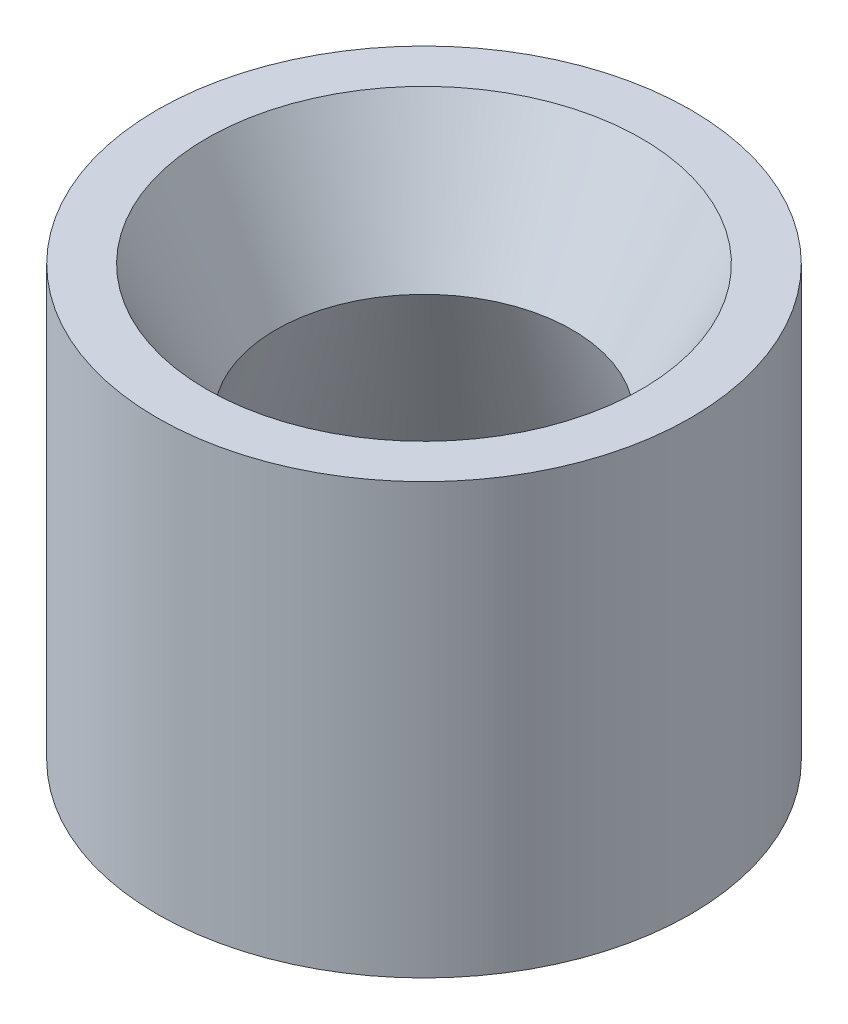
SolidWorks part; units mm, degrees
ref_plane "Front Plane" through (0, 0, 0) normal (0, 0, 1) x (1, 0, 0)
ref_plane "Top Plane" through (0, 0, 0) normal (0, 1, 0) x (1, 0, 0)
ref_plane "Right Plane" through (0, 0, 0) normal (1, 0, 0) x (0, 0, -1)
sketch "Sketch1" plane through (0, 0, 0) normal (0, 0, 1) x (1, 0, 0)
  line L0 (0, 0) -> (-27.94, 0) construction
  line L1 (-27.94, 0) -> (-34.29, 0)
  line L2 (-34.29, 0) -> (-34.29, -55.245)
  line L3 (-34.29, -55.245) -> (-33.02, -55.245)
  line L4 (-33.02, -55.245) -> (-19.05, -16.8627)
  line L5 (-19.05, -16.8627) -> (-27.94, 0)
  line L6 (0, 0) -> (0, -36.7786) construction
  dimension "D1" = 34.29
  dimension "D2" = 6.35
  dimension "D3" = 55.245
  dimension "D4" = 1.27
  dimension "D5" = 20
  dimension "D6" = 19.05
revolve "Revolve1" add sketch "Sketch1" angle 360 about L6
